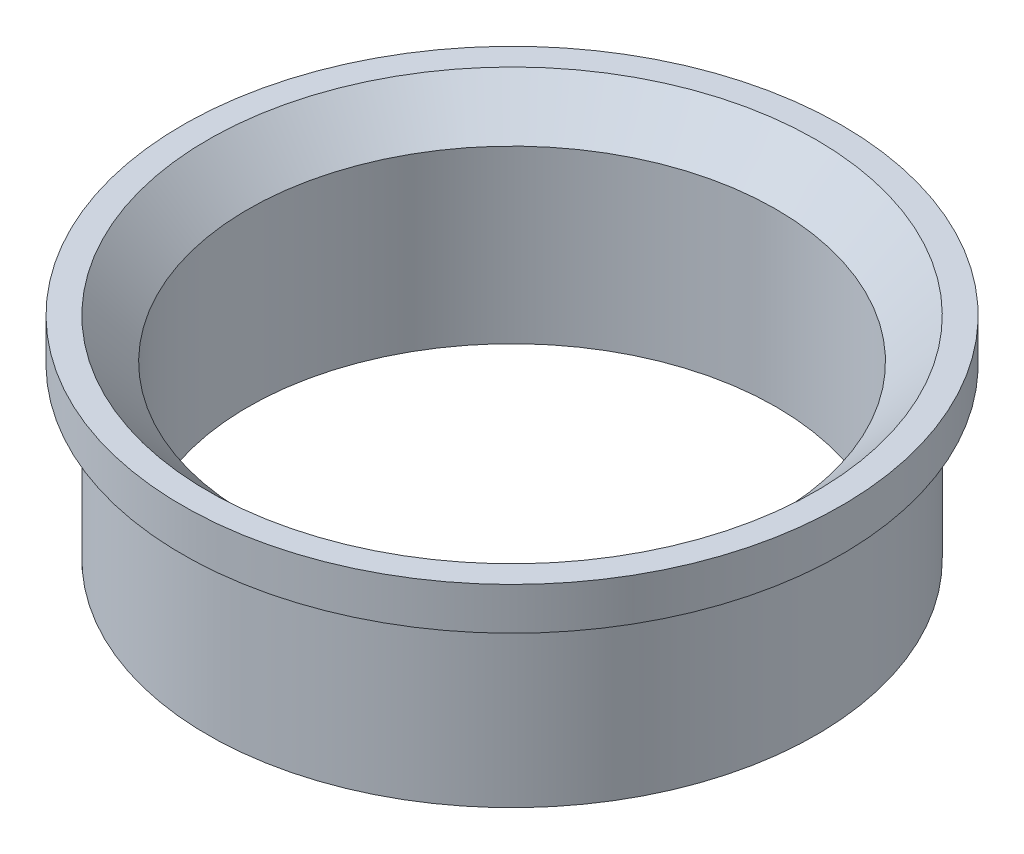
SolidWorks part; units mm, degrees
ref_plane "Front Plane" through (0, 0, 0) normal (0, 0, 1) x (1, 0, 0)
ref_plane "Top Plane" through (0, 0, 0) normal (0, 1, 0) x (1, 0, 0)
ref_plane "Right Plane" through (0, 0, 0) normal (1, 0, 0) x (0, 0, -1)
sketch "Sketch1" plane through (0, 0, 0) normal (0, 0, 1) x (1, 0, 0)
  line L0 (0, 0) -> (0, 50) construction
  line L1 (-62.5, 0) -> (-62.5, 40.5)
  line L2 (-62.5, 40.5) -> (-72, 50)
  line L3 (-72, 50) -> (-78, 50)
  line L4 (-78, 50) -> (-78, 40)
  line L5 (-78, 40) -> (-72, 40)
  line L6 (-72, 40) -> (-72, 0)
  line L7 (-72, 0) -> (-62.5, 0)
  point P5 (-68.58, 50)
  dimension "D1" = 50
  dimension "D2" = 40
  dimension "D3" = 125
  dimension "D4" = 144
  dimension "D5" = 45
  dimension "D6" = 156
  dimension "D7" = 144
revolve "Revolve1" add sketch "Sketch1" angle 360 about L0
